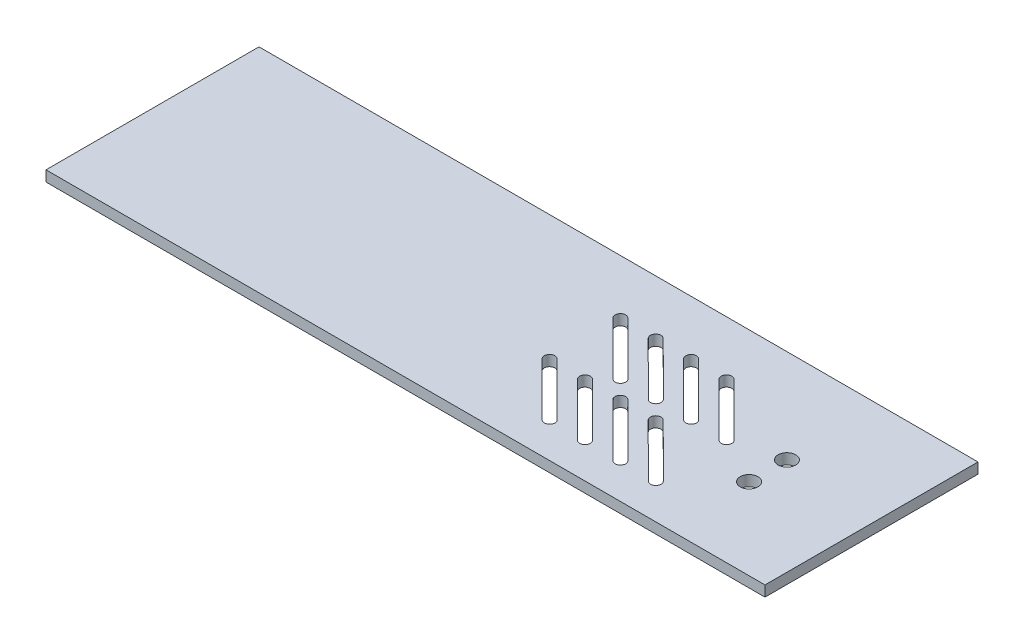
SolidWorks part; units mm, degrees
ref_plane "Front Plane" through (0, 0, 0) normal (0, 0, 1) x (1, 0, 0)
ref_plane "Top Plane" through (0, 0, 0) normal (0, 1, 0) x (1, 0, 0)
ref_plane "Right Plane" through (0, 0, 0) normal (1, 0, 0) x (0, 0, -1)
sketch "Sketch1" plane through (0, 0, 0) normal (0, 1, 0) x (1, 0, 0)
  line L0 (101.6, 30.1) -> (101.6, -30.1)
  line L1 (-101.6, 30.1) -> (101.6, 30.1)
  line L2 (-101.6, 30.1) -> (-101.6, -30.1)
  line L3 (-101.6, -30.1) -> (101.6, -30.1)
  line L5 (-101.6, 30.1) -> (101.6, -30.1) construction
  line L6 (-101.6, -30.1) -> (101.6, 30.1) construction
  point P0 (0, 0)
  dimension "D1" = 203.2
  dimension "D2" = 60.2
extrude "Boss-Extrude1" add sketch "Sketch1" along normal blind 3
sketch "Sketch5" plane through (0, 3, 0) normal (0, 1, 0) x (1, 0, 0)
  line L0 (101.6, 30.1) -> (74.1, 30.1) construction
  line L1 (101.6, 30.1) -> (-101.6, 30.1) construction
  line L2 (101.6, 30.1) -> (101.6, 3.6) construction
  line L3 (101.6, -30.1) -> (101.6, 30.1) construction
  circle A0 centre (74.1, 3.6) radius 2.5
extrude "Cut-Extrude1" cut sketch "Sketch5" against normal blind 3
sketch "Sketch7" plane through (0, 3, 0) normal (0, 1, 0) x (1, 0, 0)
  line L0 (101.6, -30.1) -> (101.6, -7.1) construction
  line L1 (101.6, -30.1) -> (101.6, 30.1) construction
  line L2 (74.1, 3.6) -> (74.1, -30.1) construction
  line L3 (-101.6, -30.1) -> (101.6, -30.1) construction
  circle A0 centre (74.1, -7.1) radius 2.5
extrude "Cut-Extrude2" cut sketch "Sketch7" against normal blind 3
sketch "Sketch8" plane through (0, 3, 0) normal (0, 1, 0) x (1, 0, 0)
  line L0 (45.8135, 14.8033) -> (60.7748, -0.1292) construction
  line L1 (46.8731, 15.865) -> (61.8345, 0.9325)
  line L2 (44.7538, 13.7416) -> (59.7152, -1.1909)
  line L3 (35.8135, 14.8033) -> (50.7748, -0.1292) construction
  line L4 (36.8731, 15.865) -> (51.8345, 0.9325)
  line L5 (34.7538, 13.7416) -> (49.7152, -1.1909)
  line L6 (25.8135, 14.8033) -> (40.7748, -0.1292) construction
  line L7 (26.8731, 15.865) -> (41.8345, 0.9325)
  line L8 (24.7538, 13.7416) -> (39.7152, -1.1909)
  line L9 (15.8135, 14.8033) -> (30.7748, -0.1292) construction
  line L10 (16.8731, 15.865) -> (31.8345, 0.9325)
  line L11 (14.7538, 13.7416) -> (29.7152, -1.1909)
  line L12 (35.8135, -5.1967) -> (50.7748, -20.1292) construction
  line L13 (36.8731, -4.135) -> (51.8345, -19.0675)
  line L14 (34.7538, -6.2584) -> (49.7152, -21.1909)
  line L15 (25.8135, -5.1967) -> (40.7748, -20.1292) construction
  line L16 (26.8731, -4.135) -> (41.8345, -19.0675)
  line L17 (24.7538, -6.2584) -> (39.7152, -21.1909)
  line L18 (15.8135, -5.1967) -> (30.7748, -20.1292) construction
  line L19 (16.8731, -4.135) -> (31.8345, -19.0675)
  line L20 (14.7538, -6.2584) -> (29.7152, -21.1909)
  line L21 (45.8135, -5.1967) -> (60.7748, -20.1292) construction
  line L22 (46.8731, -4.135) -> (61.8345, -19.0675)
  line L23 (44.7538, -6.2584) -> (59.7152, -21.1909)
  arc A0 (46.8731, 15.865) -> (44.7538, 13.7416) centre (45.8135, 14.8033) ccw
  arc A1 (59.7152, -1.1909) -> (61.8345, 0.9325) centre (60.7748, -0.1292) ccw
  arc A2 (36.8731, 15.865) -> (34.7538, 13.7416) centre (35.8135, 14.8033) ccw
  arc A3 (49.7152, -1.1909) -> (51.8345, 0.9325) centre (50.7748, -0.1292) ccw
  arc A4 (26.8731, 15.865) -> (24.7538, 13.7416) centre (25.8135, 14.8033) ccw
  arc A5 (39.7152, -1.1909) -> (41.8345, 0.9325) centre (40.7748, -0.1292) ccw
  arc A6 (16.8731, 15.865) -> (14.7538, 13.7416) centre (15.8135, 14.8033) ccw
  arc A7 (29.7152, -1.1909) -> (31.8345, 0.9325) centre (30.7748, -0.1292) ccw
  arc A8 (36.8731, -4.135) -> (34.7538, -6.2584) centre (35.8135, -5.1967) ccw
  arc A9 (49.7152, -21.1909) -> (51.8345, -19.0675) centre (50.7748, -20.1292) ccw
  arc A10 (26.8731, -4.135) -> (24.7538, -6.2584) centre (25.8135, -5.1967) ccw
  arc A11 (39.7152, -21.1909) -> (41.8345, -19.0675) centre (40.7748, -20.1292) ccw
  arc A12 (16.8731, -4.135) -> (14.7538, -6.2584) centre (15.8135, -5.1967) ccw
  arc A13 (29.7152, -21.1909) -> (31.8345, -19.0675) centre (30.7748, -20.1292) ccw
  arc A14 (46.8731, -4.135) -> (44.7538, -6.2584) centre (45.8135, -5.1967) ccw
  arc A15 (59.7152, -21.1909) -> (61.8345, -19.0675) centre (60.7748, -20.1292) ccw
  point P3 (53.2941, 7.3371)
  point P12 (43.2941, 7.3371)
  point P19 (33.2941, 7.3371)
  point P26 (23.2941, 7.3371)
  point P33 (43.2941, -12.6629)
  point P40 (33.2941, -12.6629)
  point P47 (23.2941, -12.6629)
  point P54 (53.2941, -12.6629)
  dimension "D1" = 4
  dimension "D2" = 2
extrude "Cut-Extrude3" cut sketch "Sketch8" against normal blind 3
